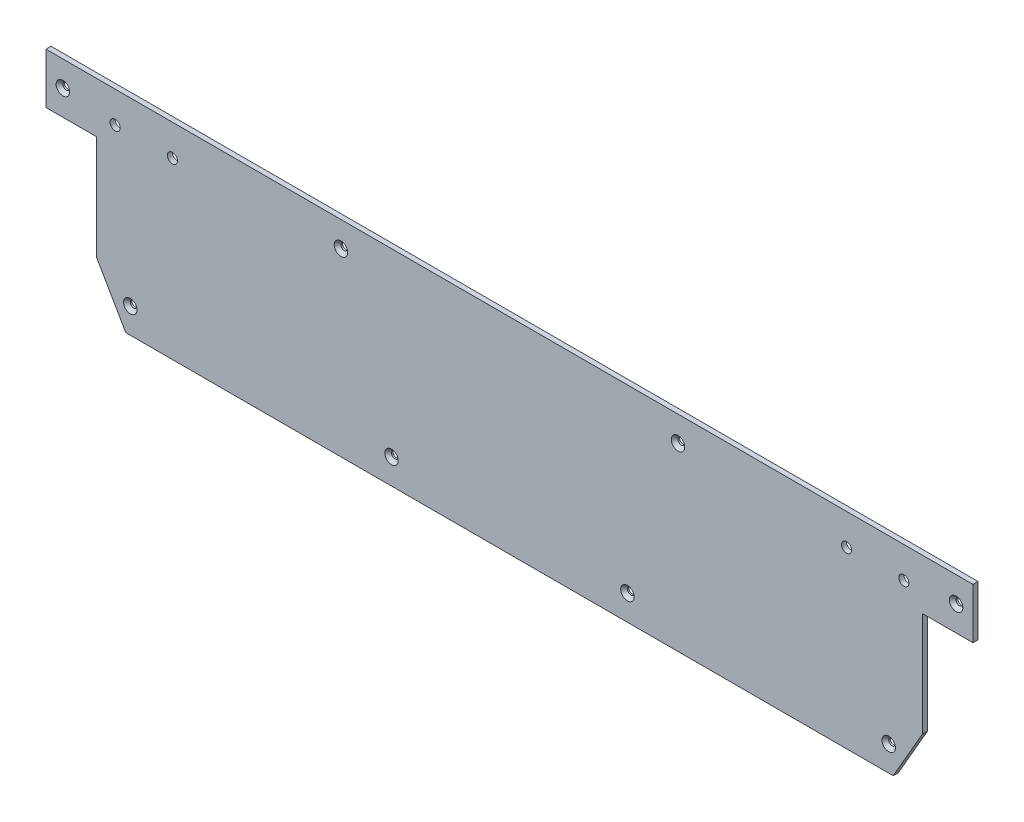
SolidWorks part; units mm, degrees
material "1060 合金"
ref_plane "前视基准面" through (0, 0, 0) normal (0, 0, 1) x (1, 0, 0)
ref_plane "上视基准面" through (0, 0, 0) normal (0, 1, 0) x (1, 0, 0)
ref_plane "右视基准面" through (0, 0, 0) normal (1, 0, 0) x (0, 0, -1)
sketch "草图1" plane through (0, 0, 0) normal (0, 0, 1) x (1, 0, 0)
  line L1 (-275, 61) -> (275, 61)
  line L2 (-275, 61) -> (-275, -61)
  line L3 (-275, -61) -> (275, -61)
  line L4 (275, 61) -> (275, -61)
  point P4 (0, -61)
  point P6 (-275, 0)
  dimension "D1" = 122
  dimension "D2" = 550
extrude "凸台-拉伸1" add sketch "草图1" along normal blind 3
sketch "草图3" plane through (0, 0, 3) normal (0, 0, 1) x (1, 0, 0)
  line L0 (-275, 61) -> (-275, -61) construction
  line L1 (-275, 31) -> (-245, 31)
  line L2 (-275, 31) -> (-275, -61)
  line L3 (-275, -61) -> (-227.6795, -61)
  line L4 (-245, 31) -> (-245, -31)
  line L5 (-275, -61) -> (275, -61) construction
  line L6 (-245, -31) -> (-227.6795, -61)
  line L7 (0, 61) -> (0, -61) construction
  line L8 (275, 61) -> (-275, 61) construction
  line L9 (245, -31) -> (227.6795, -61)
  line L10 (245, 31) -> (245, -31)
  line L11 (275, -61) -> (227.6795, -61)
  line L12 (275, 31) -> (275, -61)
  line L13 (275, 31) -> (245, 31)
  dimension "D1" = 30
  dimension "D2" = 30
  dimension "D3" = 60
  dimension "D4" = 30
extrude "切除-拉伸2" cut sketch "草图3" against normal through all
sketch "草图2" plane through (0, 0, 0) normal (0, 0, 1) x (1, 0, 0)
  line L0 (275, 61) -> (-275, 61) construction
  line L1 (0, 0) -> (0, -74.9984) construction
  line L2 (-275, 61) -> (-275, 31) construction
  line L3 (-245, -31) -> (-245, 31) construction
  line L4 (-227.6795, -61) -> (227.6795, -61) construction
  circle A0 centre (-200, 42.5) radius 3
  circle A1 centre (-234, 42.5) radius 3
  circle A2 centre (234, 42.5) radius 3
  circle A3 centre (200, 42.5) radius 3
  circle A4 centre (-265, 46) radius 2
  circle A5 centre (-100, 46) radius 2
  circle A6 centre (-225, -46) radius 2
  circle A7 centre (-70, -46) radius 2
  circle A8 centre (225, -46) radius 2
  circle A9 centre (70, -46) radius 2
  circle A10 centre (100, 46) radius 2
  circle A11 centre (265, 46) radius 2
  dimension "D2" = 6
  dimension "D5" = 4
  dimension "D1" = 34
  dimension "D3" = 200
  dimension "D4" = 18.5
  dimension "D6" = 10
  dimension "D7" = 20
  dimension "D8" = 100
  dimension "D9" = 70
  dimension "D10" = 15
  dimension "D11" = 15
extrude "切除-拉伸1" cut sketch "草图2" along normal blind 10
chamfer "倒角1" distance 2 angle 45 8 edges at (-223, -46, 3) (-68, -46, 3) (-98, 46, 3) (-263, 46, 3) (72, -46, 3) (227, -46, 3) (267, 46, 3) (102, 46, 3)
